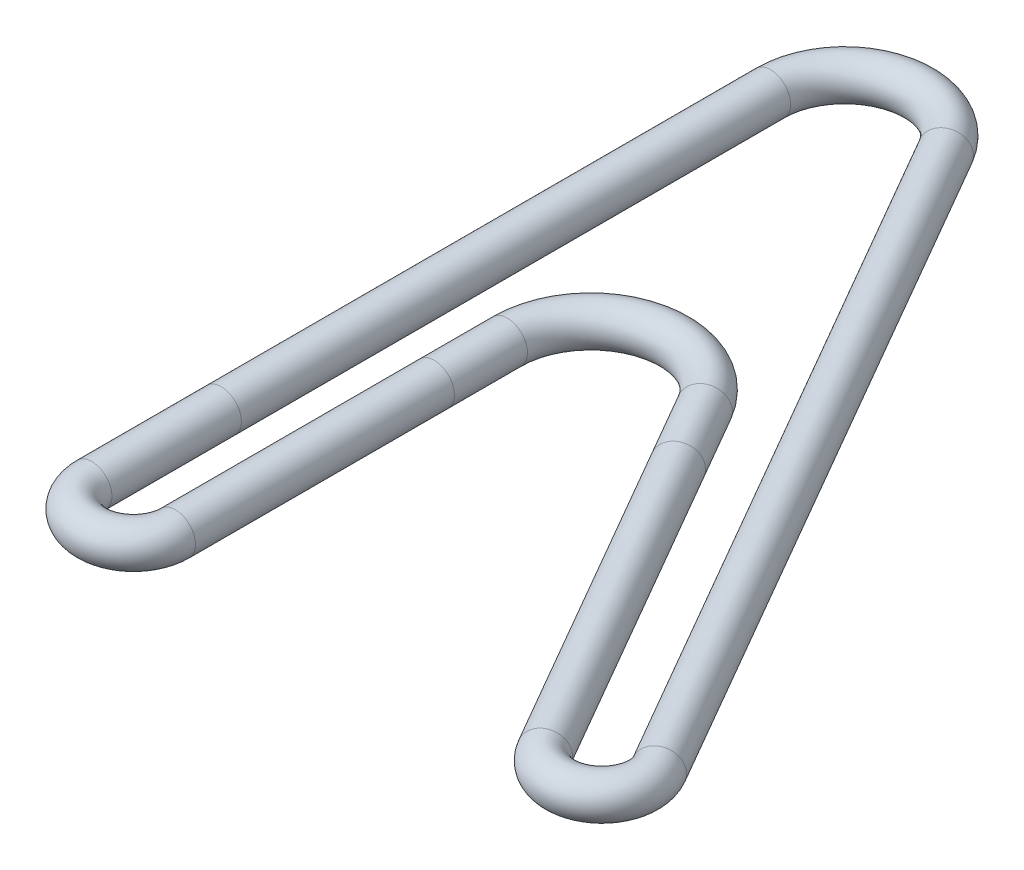
SolidWorks part; units mm, degrees
material "Plain Carbon Steel"
ref_plane "Front Plane" through (0, 0, 0) normal (0, 0, 1) x (1, 0, 0)
ref_plane "Top Plane" through (0, 0, 0) normal (0, 1, 0) x (1, 0, 0)
ref_plane "Right Plane" through (0, 0, 0) normal (1, 0, 0) x (0, 0, -1)
sketch "Sketch1" plane through (0, 0, 0) normal (0, -1, 0) x (-1, 0, 0)
  line L2 (-11.8493, 89.4617) -> (-58.0007, 9.525)
  line L4 (0, 86.2867) -> (0, 6.35)
  line L7 (-5.08, 6.35) -> (-5.08, 36.8389)
  line L8 (-32.1738, 44.0986) -> (-53.6013, 6.985)
  line L9 (-41.6085, 27.7572) -> (-46.0079, 30.2972) construction
  line L12 (-5.08, 21.5944) -> (0, 21.5944) construction
  line L18 (-32.1738, 44.0986) -> (-27.8705, 51.5521)
  line L19 (-5.08, 45.4454) -> (-5.08, 36.8389)
  arc A3 (-11.8493, 89.4617) -> (0, 86.2867) centre (-6.35, 86.2867) cw
  arc A7 (-5.08, 45.4454) -> (-27.8705, 51.5521) centre (-17.2934, 45.4454) ccw
  arc A10 (-53.6013, 6.985) -> (-58.0007, 9.525) centre (-55.801, 8.255) cw
  arc A12 (-5.08, 6.35) -> (0, 6.35) centre (-2.54, 6.35) ccw
  dimension "D2" = 5.08
  dimension "D3" = 92.303
  dimension "D4" = 12.2134
  dimension "D5" = 2.54
  dimension "D6" = 42.8551
  dimension "D11" = 6.35
  dimension "D1" = 79.9367
  dimension "D7" = 8.6065
  dimension "D8" = 30.4889
  dimension "D9" = 48.5213
  dimension "D10" = 30
  dimension "D12" = 21.5944
ref_plane "Plane1" through (0, 0, -21.5944) normal (0, 0, -1) x (-1, 0, 0)
sketch "Sketch2" plane through (0, 0, -21.5944) normal (0, 0, -1) x (-1, 0, 0)
  line L0 (0, 50) -> (0, -50) construction
  line L1 (4.7625, 0) -> (0, 0) construction
  circle A0 centre (2.3813, 0) radius 2.3812
  dimension "D1" = 4.7625
sweep "Sweep1" add profiles "Sketch2" path "Sketch1"
ref_plane "Plane2" through (0, 2.3812, 0) normal (0, 1, 0) x (1, 0, 0)
ref_plane "Plane3" through (51.7494, 0, -29.8776) normal (0.866, 0, -0.5) x (-0.5, 0, -0.866)
